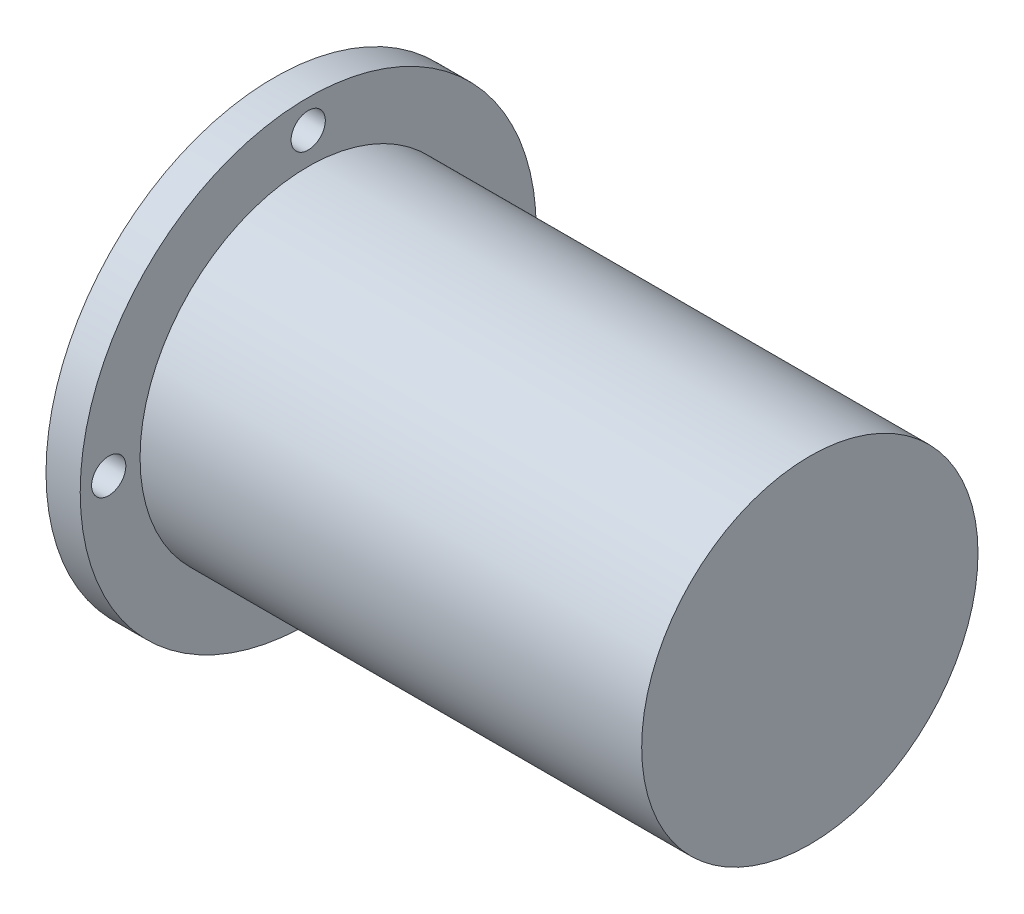
SolidWorks part; units mm, degrees
ref_plane "Front Plane" through (0, 0, 0) normal (0, 0, 1) x (1, 0, 0)
ref_plane "Top Plane" through (0, 0, 0) normal (0, 1, 0) x (1, 0, 0)
ref_plane "Right Plane" through (0, 0, 0) normal (1, 0, 0) x (0, 0, -1)
sketch "Sketch1" plane through (0, 0, 0) normal (1, 0, 0) x (0, 0, -1)
  circle A0 centre (0, 0) radius 14.75
  circle A1 centre (0, 0) radius 22.0931
  dimension "D1" = 29.5
extrude "Boss-Extrude1" add sketch "Sketch1" along normal blind 47 contours A0
sketch "Sketch2" plane through (0, 0, 0) normal (-1, 0, 0) x (0, 0, 1)
  circle A0 centre (0, 0) radius 20
  circle A5 centre (0, 0) radius 17.5 construction
  circle A6 centre (0, 17.5) radius 1.5
  circle A7 centre (17.5, 0) radius 1.5
  circle A8 centre (0, -17.5) radius 1.5
  circle A9 centre (-17.5, 0) radius 1.5
  point P15 (0, 0)
  dimension "D1" = 40
  dimension "D2" = 35
  dimension "D3" = 3
  dimension "D4" = 4
extrude "Boss-Extrude2" add sketch "Sketch2" against normal blind 3
